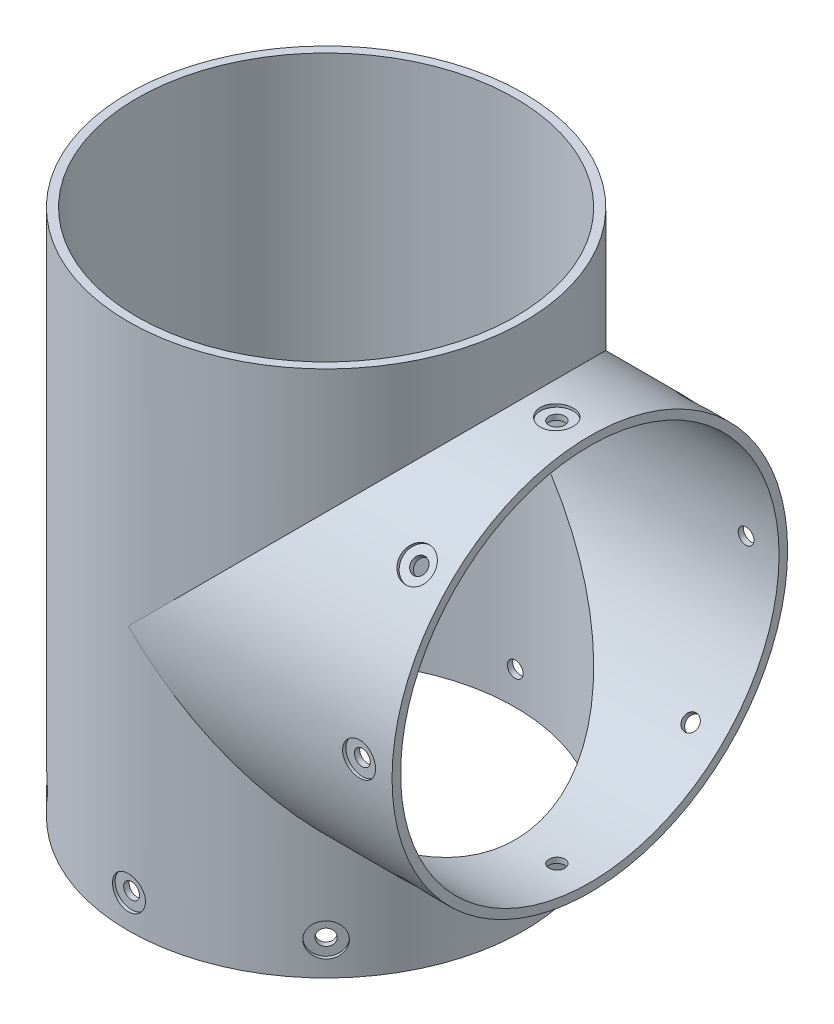
SolidWorks part; units mm, degrees
ref_plane "정면" through (0, 0, 0) normal (0, 0, 1) x (1, 0, 0)
ref_plane "윗면" through (0, 0, 0) normal (0, 1, 0) x (1, 0, 0)
ref_plane "우측면" through (0, 0, 0) normal (1, 0, 0) x (0, 0, -1)
sketch "스케치1" plane through (0, 0, 0) normal (0, 1, 0) x (1, 0, 0)
  circle A0 centre (0, 0) radius 30
  dimension "D1" = 60
extrude "보스-돌출1" add sketch "스케치1" along normal blind 80
ref_plane "평면1" through (-30, 0, 0) normal (-1, 0, 0) x (0, 0, 1)
sketch "스케치7" plane through (-30, 0, 0) normal (-1, 0, 0) x (0, 0, 1)
  point P0 (0, 5)
  dimension "D1" = 5
hole_wizard "M2 남비 머리 나사용 카운터보어1" positions "스케치8" profile "스케치9" counterbore size "M2" standard "ISO"
sketch "스케치8" plane through (-30, 0, 0) normal (-1, 0, 0) x (0, 0, 1)
  point P0 (0, 5)
sketch "스케치9" plane through (-30, 5, 0) normal (0, 1, 0) x (0, 0, 1)
  line L0 (0, 0) -> (0, 10.721)
  line L1 (0, 10.721) -> (1.2, 10)
  line L2 (1.2, 10) -> (1.2, 0.5)
  line L3 (1.2, 0.5) -> (2.5, 0.5)
  line L4 (2.5, 0.5) -> (2.5, 0)
  line L5 (2.5, 0) -> (0, 0)
  line L10 (0, 10.721) -> (-1.2, 10) construction
  line L11 (0, -6.35) -> (0, 107.95) construction
  dimension "구멍 지름" = 2.4
  dimension "구멍 깊이" = 10
  dimension "카운터보어 지름" = 5
  dimension "카운터보어 깊이" = 0.5
  dimension "드릴 각도" = 118
pattern_circular "원형 패턴1" count 8 over 360 about axis through (0, 0, 0) along (0, 1, 0) of "M2 남비 머리 나사용 카운터보어1"
sketch "스케치10" plane through (0, 0, 0) normal (1, 0, 0) x (0, 0, -1)
  circle A0 centre (0, 40) radius 30
  dimension "D1" = 60
  dimension "D2" = 40
extrude "보스-돌출2" add sketch "스케치10" along normal blind 40
sketch "스케치11" plane through (40, 0, 0) normal (1, 0, 0) x (0, 0, -1)
  circle A0 centre (0, 40) radius 28.7
  arc A1 (30, 40) -> (-30, 40) centre (0, 40) ccw construction
  dimension "D1" = 1.3
extrude "컷-돌출2" cut sketch "스케치11" against normal blind 40 contours A0
sketch "스케치12" plane through (0, 80, 0) normal (0, 1, 0) x (1, 0, 0)
  circle A0 centre (0, 0) radius 28.7
  arc A1 (0, -30) -> (0, 30) centre (0, 0) ccw construction
  dimension "D1" = 1.3
extrude "컷-돌출3" cut sketch "스케치12" against normal through all
ref_plane "평면2" through (0, 70, 0) normal (0, -1, 0) x (-1, 0, 0)
sketch "스케치13" plane through (0, 70, 0) normal (0, -1, 0) x (-1, 0, 0)
  line L0 (-40, 30) -> (-40, -30) construction
  point P0 (-35, 0)
  dimension "D1" = 5
hole_wizard "M2 남비 머리 나사용 카운터보어2" positions "스케치14" profile "스케치15" counterbore size "M2" standard "ISO"
sketch "스케치14" plane through (0, 70, 0) normal (0, -1, 0) x (-1, 0, 0)
  point P0 (-35, 0)
sketch "스케치15" plane through (35, 70, 0) normal (1, 0, 0) x (0, 0, 1)
  line L0 (0, 0) -> (0, 10.721)
  line L1 (0, 10.721) -> (1.2, 10)
  line L2 (1.2, 10) -> (1.2, 0.5)
  line L3 (1.2, 0.5) -> (2.5, 0.5)
  line L4 (2.5, 0.5) -> (2.5, 0)
  line L5 (2.5, 0) -> (0, 0)
  line L10 (0, 10.721) -> (-1.2, 10) construction
  line L11 (0, -6.35) -> (0, 107.95) construction
  dimension "구멍 지름" = 2.4
  dimension "구멍 깊이" = 10
  dimension "카운터보어 지름" = 5
  dimension "카운터보어 깊이" = 0.5
  dimension "드릴 각도" = 118
pattern_circular "원형 패턴2" count 8 over 360 about axis through (0, 40, 0) along (1, 0, 0) of "M2 남비 머리 나사용 카운터보어2"
